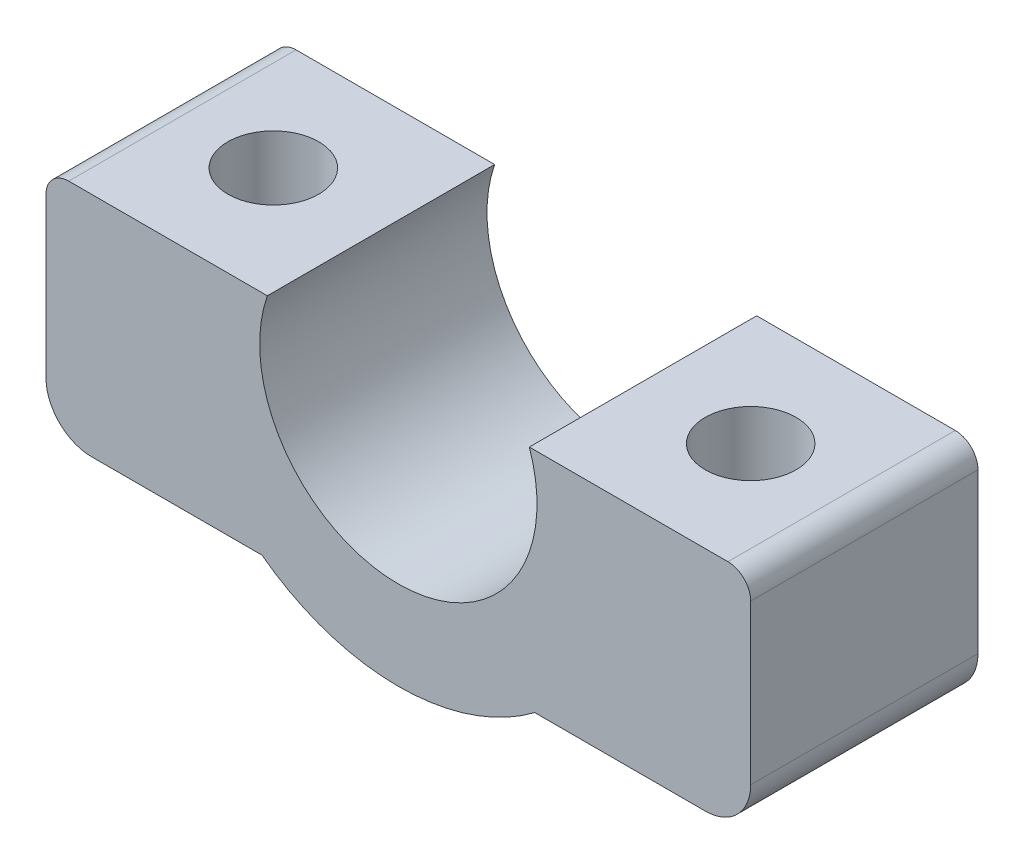
SolidWorks part; units mm, degrees
material "6063-O, 押出棒 (SS)"
ref_plane "正面" through (0, 0, 0) normal (0, 0, 1) x (1, 0, 0)
ref_plane "平面" through (0, 0, 0) normal (0, 1, 0) x (1, 0, 0)
ref_plane "右側面" through (0, 0, 0) normal (1, 0, 0) x (0, 0, -1)
sketch "ｽｹｯﾁ1" plane through (0, 0, 0) normal (0, 0, 1) x (1, 0, 0)
  circle A0 centre (0, 0) radius 15
  dimension "D1" = 30
extrude "ﾎﾞｽ - 押し出し1" add sketch "ｽｹｯﾁ1" along normal blind 10
sketch "ｽｹｯﾁ2" plane through (0, 0, 10) normal (0, 0, 1) x (1, 0, 0)
  line L0 (5.7628, 2) -> (20.1459, 2)
  line L1 (-19.8541, 2) -> (-5.7628, 2)
  line L2 (-19.8541, 2) -> (-19.8541, 26.7489)
  line L3 (-19.8541, 26.7489) -> (20.1459, 26.7489)
  line L4 (20.1459, 2) -> (20.1459, 26.7489)
  arc A0 (-5.7628, 2) -> (5.7628, 2) centre (0, 0) ccw
  point P3 (0, 6.1)
  dimension "D1" = 12.2
  dimension "D2" = 40
  dimension "D3" = 2
extrude "ｶｯﾄ - 押し出し1" cut sketch "ｽｹｯﾁ2" against normal blind 10
sketch "ｽｹｯﾁ5" plane through (0, 2, 0) normal (0, 1, 0) x (1, 0, 0)
  line L0 (-14.8661, -5) -> (14.8661, -5) construction
  line L1 (-14.8661, -10) -> (-14.8661, 0) construction
  line L2 (14.8661, 0) -> (14.8661, -10) construction
  line L3 (0, 0) -> (0, -10) construction
  line L4 (6.1, 0) -> (-6.1, 0) construction
  line L5 (-6.1, -10) -> (6.1, -10) construction
  circle A0 centre (-10.5, -5) radius 2
  circle A1 centre (10.5, -5) radius 2
  dimension "D1" = 21
  dimension "D2" = 4
extrude "ｶｯﾄ - 押し出し2" cut sketch "ｽｹｯﾁ5" against normal through all
sketch "ｽｹｯﾁ7" plane through (0, 0, 10) normal (0, 0, 1) x (1, 0, 0)
  line L0 (0, 0) -> (0, -50000) construction
  line L1 (5.7628, 2) -> (14.8661, 2) construction
  line L2 (-15.3243, -18.6888) -> (15.3243, -18.6888)
  line L3 (-15.3243, -18.6888) -> (-15.3243, -8)
  line L4 (-15.3243, -8) -> (15.3243, -8)
  line L5 (15.3243, -18.6888) -> (15.3243, -8)
  line L6 (-15.3243, -18.6888) -> (15.3243, -8) construction
  line L7 (-15.3243, -8) -> (15.3243, -18.6888) construction
  point P3 (0, -13.3444)
  dimension "D1" = 10
extrude "ｶｯﾄ - 押し出し4" cut sketch "ｽｹｯﾁ7" against normal through all
sketch "ｽｹｯﾁ8" plane through (0, 0, 10) normal (0, 0, 1) x (1, 0, 0)
  line L0 (5.7628, 2) -> (14.8661, 2) construction
  line L1 (-15.5, 2) -> (15.5, 2)
  line L2 (-15.5, 2) -> (-15.5, -8)
  line L3 (-15.5, -8) -> (15.5, -8)
  line L4 (15.5, 2) -> (15.5, -8)
  line L5 (0, 0) -> (0, -50000) construction
  line L6 (12.6886, -8) -> (-12.6886, -8) construction
  arc A0 (-5.7628, 2) -> (5.7628, 2) centre (0, 0) ccw construction
  arc A1 (-5.7628, 2) -> (5.7628, 2) centre (0, 0) ccw
  arc M5 (12.6886, -8) -> (14.8661, 2) centre (0, 0) ccw
  arc M9 (-14.8661, 2) -> (-12.6886, -8) centre (0, 0) ccw
  dimension "D1" = 31
extrude "ﾎﾞｽ - 押し出し2" add sketch "ｽｹｯﾁ8" against normal up to surface (10 mm away) contours L2 L3 M9 | L4 L3 M5
sketch "ｽｹｯﾁ9" plane through (0, 0, 10) normal (0, 0, 1) x (1, 0, 0)
  line L0 (-6, -8) -> (6, -8)
  line L1 (15.5, -8) -> (-15.5, -8) construction
  arc A0 (-6, -8) -> (6, -8) centre (0, 0) ccw
  dimension "D1" = 20
extrude "ﾎﾞｽ - 押し出し3" add sketch "ｽｹｯﾁ9" against normal up to surface (10 mm away) up to face at (0, -2.6833, 0)
fillet "ﾌｨﾚｯﾄ1" radius 2 2 edges at (-15.5, -8, 5) (15.5, -8, 5)
fillet "ﾌｨﾚｯﾄ2" radius 1 2 edges at (-15.5, 2, 5) (15.5, 2, 5)
